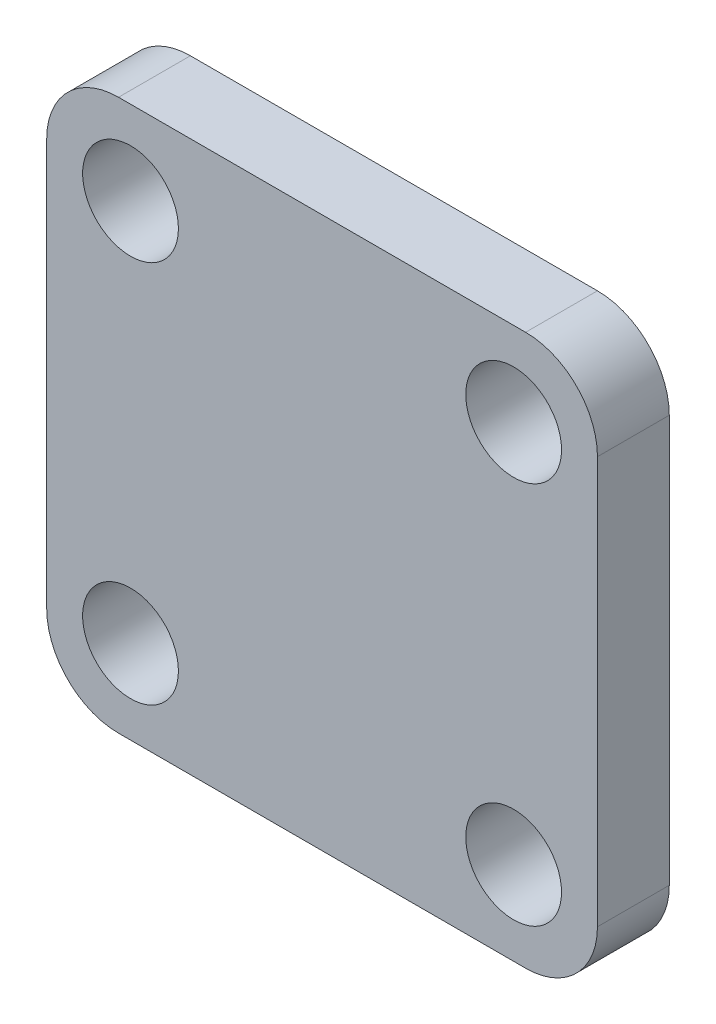
SolidWorks part; units mm, degrees
material "PLA Density Only"
ref_plane "Front Plane" through (0, 0, 0) normal (0, 0, 1) x (1, 0, 0)
ref_plane "Top Plane" through (0, 0, 0) normal (0, 1, 0) x (1, 0, 0)
ref_plane "Right Plane" through (0, 0, 0) normal (1, 0, 0) x (0, 0, -1)
sketch "Sketch1" plane through (0, 0, 0) normal (0, 0, 1) x (1, 0, 0)
  line L1 (-8.5, 11.5) -> (8.5, 11.5)
  line L2 (-11.5, 8.5) -> (-11.5, -8.5)
  line L3 (-8.5, -11.5) -> (8.5, -11.5)
  line L4 (11.5, 8.5) -> (11.5, -8.5)
  line L5 (-11.5, 11.5) -> (11.5, -11.5) construction
  line L6 (-11.5, -11.5) -> (11.5, 11.5) construction
  arc A0 (-11.5, -8.5) -> (-8.5, -11.5) centre (-8.5, -8.5) ccw
  arc A1 (8.5, -11.5) -> (11.5, -8.5) centre (8.5, -8.5) ccw
  arc A2 (8.5, 11.5) -> (11.5, 8.5) centre (8.5, 8.5) cw
  arc A3 (-8.5, 11.5) -> (-11.5, 8.5) centre (-8.5, 8.5) ccw
  circle A4 centre (-8, 8) radius 2
  circle A5 centre (8, 8) radius 2
  circle A6 centre (8, -8) radius 2
  circle A7 centre (-8, -8) radius 2
  point P29 (0, 0)
  dimension "D2" = 3
  dimension "4" = 4
  dimension "D1" = 23
  dimension "D4" = 16
extrude "Boss-Extrude1" add sketch "Sketch1" along normal blind 3
